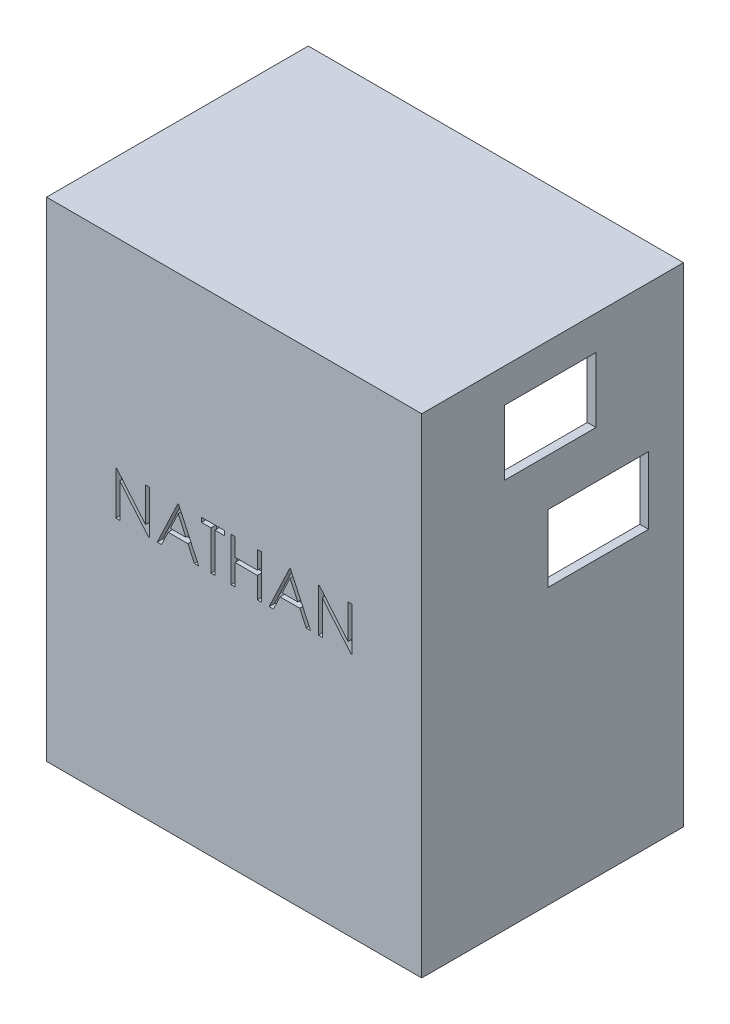
SolidWorks part; units mm, degrees
ref_plane "Plan de face" through (0, 0, 0) normal (0, 0, 1) x (1, 0, 0)
ref_plane "Plan de dessus" through (0, 0, 0) normal (0, 1, 0) x (1, 0, 0)
ref_plane "Plan de droite" through (0, 0, 0) normal (1, 0, 0) x (0, 0, -1)
sketch "Esquisse1" plane through (0, 0, 0) normal (0, 0, 1) x (1, 0, 0)
  line L1 (0, 0) -> (86, 0)
  line L2 (0, 0) -> (0, 94)
  line L3 (0, 94) -> (86, 94)
  line L4 (86, 0) -> (86, 94)
  dimension "D1" = 86
  dimension "D2" = 94
extrude "Boss.-Extru.1" add sketch "Esquisse1" along normal blind 60
sketch "Esquisse2" plane through (0, 0, 0) normal (0, 0, 1) x (1, 0, 0)
  line L0 (0, 94) -> (0, 0) construction
  line L1 (2, 92) -> (84, 92)
  line L2 (2, 92) -> (2, 2)
  line L3 (2, 2) -> (84, 2)
  line L4 (84, 92) -> (84, 2)
  line L5 (86, 0) -> (86, 94) construction
  line L6 (0, 0) -> (86, 0) construction
  line L7 (86, 94) -> (0, 94) construction
  dimension "D1" = 2
  dimension "D2" = 2
  dimension "D3" = 2
  dimension "D4" = 2
  dimension "D5" = 90
  dimension "D6" = 82
extrude "Enlèv. mat.-Extru.1" cut sketch "Esquisse2" along normal blind 58
sketch "Esquisse3" plane through (0, 94, 0) normal (0, 1, 0) x (1, 0, 0)
  line L0 (86, -60) -> (0, -60) construction
  line L1 (0, 0) -> (86, 0)
  line L2 (0, 0) -> (0, -60)
  line L3 (0, -60) -> (86, -60)
  line L4 (86, 0) -> (86, -60)
  line L5 (86, -60) -> (86, 0) construction
extrude "Boss.-Extru.2" add sketch "Esquisse3" along normal blind 18
ref_plane "Plan1" through (0, 92, 0) normal (0, 1, 0) x (1, 0, 0)
sketch "Esquisse5" plane through (0, 92, 0) normal (0, 1, 0) x (1, 0, 0)
  line L0 (0, 0) -> (0, -60) construction
  line L1 (2, -2) -> (84, -2)
  line L2 (2, -2) -> (2, -58)
  line L3 (2, -58) -> (84, -58)
  line L4 (84, -2) -> (84, -58)
  line L5 (86, 0) -> (0, 0) construction
  line L6 (86, -60) -> (86, 0) construction
  line L7 (0, -60) -> (86, -60) construction
  dimension "D1" = 2
  dimension "D2" = 2
  dimension "D3" = 2
  dimension "D4" = 2
extrude "Enlèv. mat.-Extru.2" cut sketch "Esquisse5" along normal blind 18
sketch "Esquisse7" plane through (86, 0, 0) normal (1, 0, 0) x (0, 0, -1)
  line L0 (-80.735, 63.0599) -> (39.2837, 63.0599) construction
  line L2 (-8, 122.3986) -> (-8, -15.9053) construction
  line L4 (-80.735, 78.4999) -> (9.672, 78.4999) construction
  line L6 (-31, 122.3986) -> (-31, -15.9053) construction
  line L12 (-60, 0) -> (-60, 112) construction
  line L13 (-31, 78.4999) -> (-8, 78.4999)
  line L14 (-31, 78.4999) -> (-31, 63.0599)
  line L15 (-31, 63.0599) -> (-8, 63.0599)
  line L16 (-8, 78.4999) -> (-8, 63.0599)
  dimension "D1" = 29
extrude "Enlèv. mat.-Extru.3" cut sketch "Esquisse7" against normal blind 18 and the other way through all
sketch "Esquisse8" plane through (0, 0, 0) normal (-1, 0, 0) x (0, 0, 1)
  line L0 (-12.4506, 48) -> (82.8584, 48) construction
  line L1 (0, 112) -> (60, 112) construction
  line L2 (-13.4802, 79) -> (81.3875, 79) construction
  line L3 (13.5, 134.6829) -> (13.5, -17.3879) construction
  line L4 (60, 112) -> (60, 0) construction
  line L5 (28, 134.6829) -> (28, -17.3879) construction
  line L6 (0, 112) -> (0, 0) construction
  line L7 (13.5, 79) -> (28, 79)
  line L8 (13.5, 79) -> (13.5, 48)
  line L9 (13.5, 48) -> (28, 48)
  line L10 (28, 79) -> (28, 48)
  dimension "D1" = 64
  dimension "D2" = 33
  dimension "D3" = 13.5
  dimension "D4" = 32
  dimension "D5" = 14.5
  dimension "D6" = 31
extrude "Enlèv. mat.-Extru.4" cut sketch "Esquisse8" against normal blind 18
sketch "Esquisse11" plane through (86, 0, 0) normal (1, 0, 0) x (0, 0, -1)
  line L5 (-41.0096, 104.2007) -> (-20.0596, 104.2007)
  line L6 (-41.0096, 104.2007) -> (-41.0096, 89.3007)
  line L7 (-41.0096, 89.3007) -> (-20.0596, 89.3007)
  line L8 (-20.0596, 104.2007) -> (-20.0596, 89.3007)
  dimension "D1" = 14.9
  dimension "D2" = 20.95
extrude "Enlèv. mat.-Extru.5" cut sketch "Esquisse11" against normal blind 18
sketch "Esquisse12" plane through (0, 0, 0) normal (0, -1, 0) x (1, 0, 0)
  circle A0 centre (36.4618, 26.6887) radius 3.095
  dimension "D1" = 6.19
extrude "Enlèv. mat.-Extru.6" cut sketch "Esquisse12" against normal blind 18 contours A0
sketch "Esquisse15" plane through (0, 0, 58) normal (0, 0, -1) x (-1, 0, 0)
  line L0 (-43, 92) -> (-43, 2) construction
  line L1 (-84, 92) -> (-2, 92) construction
  line L2 (-2, 2) -> (-84, 2) construction
  line L3 (-98.8963, 47) -> (17.9978, 47) construction
  circle A0 centre (-77.525, 7.9638) radius 3
  circle A1 centre (-8.475, 7.9638) radius 3
  circle A2 centre (-77.525, 86.0362) radius 3
  circle A3 centre (-8.475, 86.0362) radius 3
  dimension "D1" = 6
extrude "Boss.-Extru.3" add sketch "Esquisse15" along normal blind 18
sketch "Esquisse16" plane through (0, 0, 60) normal (0, 0, 1) x (1, 0, 0)
  text T0 "NATHAN" font "Century Gothic" height 10
extrude "Enlèv. mat.-Extru.7" cut sketch "Esquisse16" against normal blind 1.3
